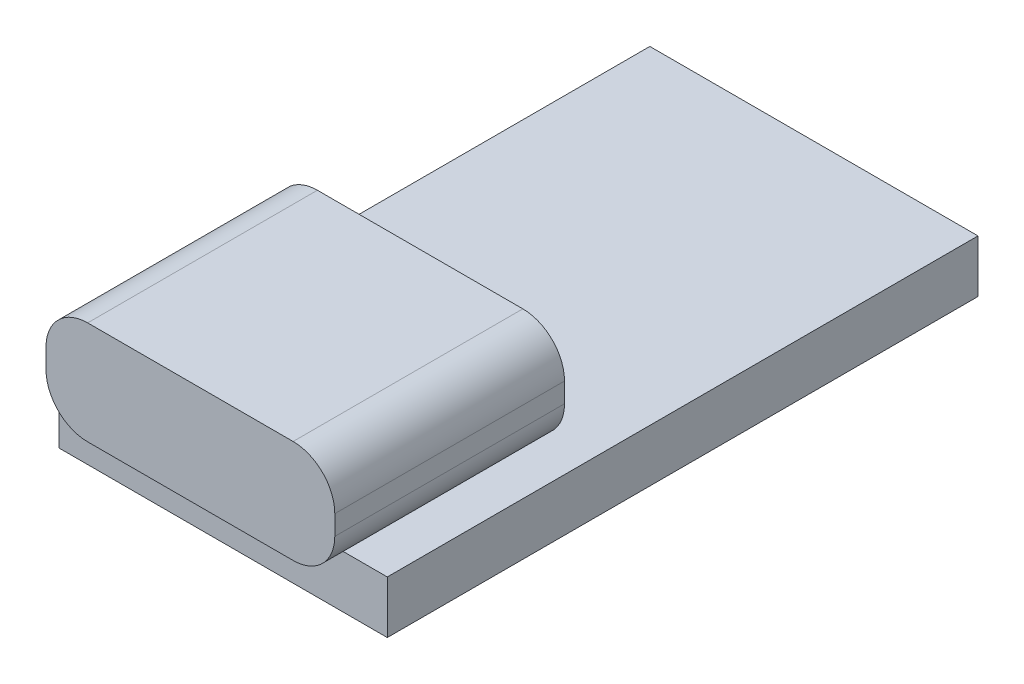
SolidWorks part; units mm, degrees
material "Epoxy, Unfilled"
ref_plane "Front Plane" through (0, 0, 0) normal (0, 0, 1) x (1, 0, 0)
ref_plane "Top Plane" through (0, 0, 0) normal (0, 1, 0) x (1, 0, 0)
ref_plane "Right Plane" through (0, 0, 0) normal (1, 0, 0) x (0, 0, -1)
sketch "Sketch1" plane through (0, 0, 0) normal (0, 1, 0) x (1, 0, 0)
  line L1 (0, 0) -> (10, 0)
  line L2 (0, 0) -> (0, 18)
  line L3 (0, 18) -> (10, 18)
  line L4 (10, 0) -> (10, 18)
  dimension "D1" = 10
  dimension "D2" = 18
extrude "Boss-Extrude1" add sketch "Sketch1" along normal blind 1.6
ref_plane "Plane1" through (0, 0, 1) normal (0, 0, 1) x (1, 0, 0)
sketch "Sketch3" plane through (0, 0, 1) normal (0, 0, 1) x (1, 0, 0)
  line L0 (0.6, 3.17) -> (9.4, 3.17) construction
  line L3 (1.87, 4.74) -> (8.13, 4.74)
  line L4 (0.6, 3.47) -> (0.6, 2.87)
  line L5 (1.87, 1.6) -> (8.13, 1.6)
  line L6 (9.4, 3.47) -> (9.4, 2.87)
  line L7 (0, 1.6) -> (10, 1.6) construction
  line L8 (0, 0) -> (10, 0) construction
  arc A2 (8.13, 4.74) -> (9.4, 3.47) centre (8.13, 3.47) cw
  arc A3 (8.13, 1.6) -> (9.4, 2.87) centre (8.13, 2.87) ccw
  arc A4 (0.6, 2.87) -> (1.87, 1.6) centre (1.87, 2.87) ccw
  arc A5 (1.87, 4.74) -> (0.6, 3.47) centre (1.87, 3.47) ccw
  point P16 (5, 3.17)
  point P17 (5, 1.6)
  dimension "D1" = 3.14
  dimension "D2" = 0.6
  dimension "D3" = 3.17
  dimension "D4" = 8.8
extrude "Boss-Extrude2" add sketch "Sketch3" against normal blind 7
